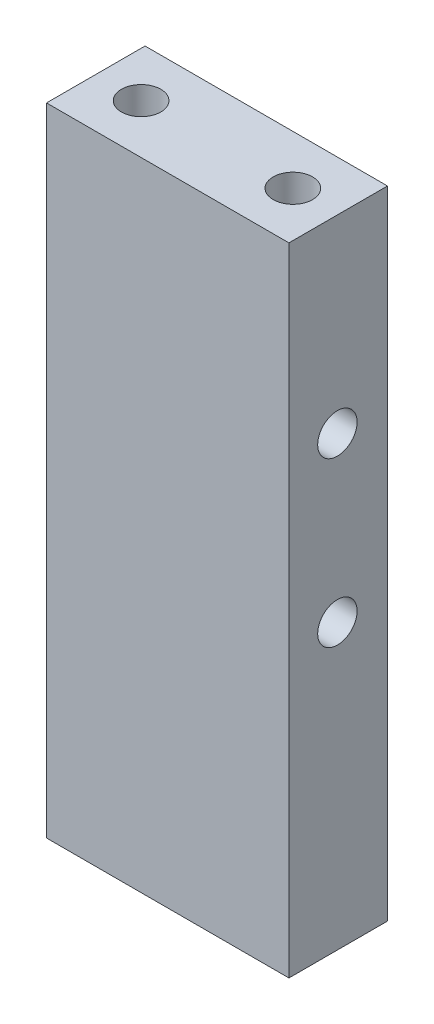
SolidWorks part; units mm, degrees
ref_plane "Front Plane" through (0, 0, 0) normal (0, 0, 1) x (1, 0, 0)
ref_plane "Top Plane" through (0, 0, 0) normal (0, 1, 0) x (1, 0, 0)
ref_plane "Right Plane" through (0, 0, 0) normal (1, 0, 0) x (0, 0, -1)
other "Graphic1"
other "object_1 (Open) -1"
ref_plane "Plane1" through (0, 0, 6) normal (0, 0, 1) x (1, 0, 0)
sketch "Sketch1" plane through (0, 0, 6) normal (0, 0, 1) x (1, 0, 0)
  line L1 (-246.4266, 284.5112) -> (-234.1266, 284.5112)
  line L2 (-246.4266, 284.5112) -> (-246.4266, 252.2112)
  line L3 (-246.4266, 252.2112) -> (-234.1266, 252.2112)
  line L4 (-234.1266, 284.5112) -> (-234.1266, 252.2112)
  dimension "D1" = 12.3
  dimension "D2" = 32.3
extrude "Boss-Extrude1" add sketch "Sketch1" along normal blind 5
sketch "Sketch3" plane through (-246.4266, 0, 0) normal (-1, 0, 0) x (0, 0, 1)
  line L0 (11, 284.5112) -> (6, 284.5112) construction
  circle A0 centre (8.5422, 274.9112) radius 1
  circle A1 centre (8.5422, 266.6112) radius 1
  dimension "D1" = 2
  dimension "D3" = 2
  dimension "D2" = 9.6
  dimension "D4" = 8.3
extrude "Cut-Extrude1" cut sketch "Sketch3" against normal through all
sketch "Sketch4" plane through (0, 252.2112, 0) normal (0, -1, 0) x (-1, 0, 0)
  line L0 (234.1266, -11) -> (234.1266, -6) construction
  line L2 (-12.101, -6) -> (12.101, -6) construction
  circle A0 centre (244.1266, -8.5) radius 1
  circle A1 centre (236.4266, -8.5) radius 1
  point P6 (0, 0)
  dimension "D1" = 7.7
  dimension "D2" = 2.3
  dimension "D3" = 2.5
extrude "Cut-Extrude2" cut sketch "Sketch4" against normal through all
